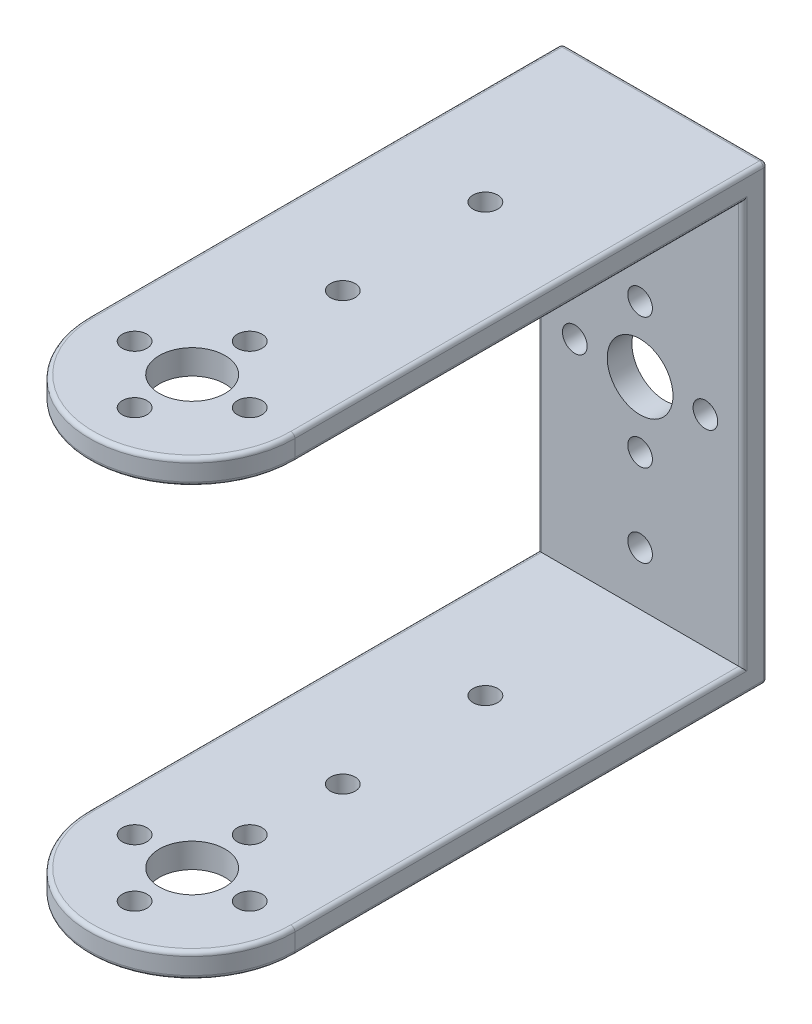
SolidWorks part; units mm, degrees
ref_plane "Front Plane" through (0, 0, 0) normal (0, 0, 1) x (1, 0, 0)
ref_plane "Top Plane" through (0, 0, 0) normal (0, 1, 0) x (1, 0, 0)
ref_plane "Right Plane" through (0, 0, 0) normal (1, 0, 0) x (0, 0, -1)
sketch "Sketch1" plane through (0, 0, 0) normal (0, 0, 1) x (1, 0, 0)
  line L1 (-12.5, 27.5) -> (12.5, 27.5)
  line L2 (-12.5, 27.5) -> (-12.5, -27.5)
  line L3 (-12.5, -27.5) -> (12.5, -27.5)
  line L4 (12.5, 27.5) -> (12.5, -27.5)
  line L5 (-12.5, 27.5) -> (12.5, -27.5) construction
  line L6 (-12.5, -27.5) -> (12.5, 27.5) construction
  point P0 (0, 0)
  dimension "D1" = 25
  dimension "D2" = 55
extrude "Boss-Extrude1" add sketch "Sketch1" along normal blind 3
hole_wizard "Ø8.0mm Dowel Hole1" positions "Sketch2" profile "Sketch3" hole size "Ø8.0" standard "ISO"
sketch "Sketch2" plane through (0, 0, 3) normal (0, 0, 1) x (1, 0, 0)
  point P0 (0, 0)
sketch "Sketch3" plane through (0, 0, 3) normal (1, 0, 0) x (0, -1, 0)
  line L0 (0, 0) -> (0, 5.4034)
  line L1 (0, 5.4034) -> (4, 3)
  line L2 (4, 3) -> (4, 0)
  line L5 (4, 0) -> (0, 0)
  line L10 (0, 5.4034) -> (-4, 3) construction
  line L11 (0, -6.35) -> (0, 107.95) construction
  dimension "Hole Dia." = 8
  dimension "Hole Depth" = 3
  dimension "Drill Angle" = 118
hole_wizard "Ø3.0mm Dowel Hole1" positions "Sketch4" profile "Sketch5" hole size "Ø3.0" standard "ISO"
sketch "Sketch4" plane through (0, 0, 3) normal (0, 0, 1) x (1, 0, 0)
  point P0 (0, -7.9463)
  point P6 (-7.9463, 0)
  point P7 (0, 7.9463)
  point P8 (7.9463, 0)
  point P9 (0, 0)
  point P10 (0, 18)
  point P18 (0, -36)
  point P19 (0, -18)
  dimension "D2" = 18
  dimension "D3" = 2
  dimension "D1" = 4
sketch "Sketch5" plane through (0, -7.9463, 3) normal (1, 0, 0) x (0, -1, 0)
  line L0 (0, 0) -> (0, 3.9013)
  line L1 (0, 3.9013) -> (1.5, 3)
  line L2 (1.5, 3) -> (1.5, 0)
  line L5 (1.5, 0) -> (0, 0)
  line L10 (0, 3.9013) -> (-1.5, 3) construction
  line L11 (0, -6.35) -> (0, 107.95) construction
  dimension "Hole Dia." = 3
  dimension "Hole Depth" = 3
  dimension "Drill Angle" = 118
sketch "Sketch6" plane through (0, 0, 3) normal (0, 0, 1) x (1, 0, 0)
  line L0 (12.5, -27.5) -> (12.5, 27.5) construction
  line L1 (-12.5, 27.5) -> (12.5, 27.5)
  line L2 (-12.5, 27.5) -> (-12.5, 24.5)
  line L3 (-12.5, 24.5) -> (12.5, 24.5)
  line L4 (12.5, 27.5) -> (12.5, 24.5)
  line L5 (-12.5, -24.5) -> (-12.5, -27.5)
  line L6 (-12.5, -24.5) -> (12.5, -24.5)
  line L7 (12.5, -24.5) -> (12.5, -27.5)
  line L8 (-12.5, -27.5) -> (12.5, -27.5)
  dimension "D1" = 3
  dimension "D2" = 2
extrude "Boss-Extrude2" add sketch "Sketch6" along normal blind 67
sketch "Sketch8" plane through (0, 27.5, 0) normal (0, 1, 0) x (1, 0, 0)
  line L2 (-12.5, -70) -> (12.5, -70)
  line L3 (-12.5, -70) -> (-12.5, -57.5)
  line L5 (12.5, -70) -> (12.5, -57.5)
  arc A0 (-12.5, -57.5) -> (12.5, -57.5) centre (0, -57.5) ccw
  line M4 (-12.5, 0) -> (-12.5, -70)
  line M5 (-12.5, -70) -> (12.5, -70)
  line M6 (12.5, -70) -> (12.5, 0)
extrude "Cut-Extrude2" cut sketch "Sketch8" against normal through all contours A0 M4 M5 | A0 L2 M6
hole_wizard "Ø8.0mm Dowel Hole2" positions "Sketch9" profile "Sketch11" hole size "Ø8.0" standard "ISO" end condition through all
sketch "Sketch9" plane through (0, 27.5, 0) normal (0, 1, 0) x (1, 0, 0)
  point P0 (0, -57.5)
sketch "Sketch11" plane through (0, 27.5, 57.5) normal (1, 0, 0) x (0, 0, 1)
  line L0 (0, 0) -> (0, 55)
  line L1 (0, 55) -> (4, 55)
  line L2 (4, 55) -> (4, 0)
  line L5 (4, 0) -> (0, 0)
  line L11 (0, -6.35) -> (0, 107.95) construction
  dimension "Thru Hole Dia." = 8
  dimension "Thru Hole Depth" = 55
hole_wizard "Ø3.0mm Dowel Hole2" positions "Sketch12" profile "Sketch13" hole size "Ø3.0" standard "ISO" end condition through all
sketch "Sketch12" plane through (0, 27.5, 0) normal (0, 1, 0) x (1, 0, 0)
  circle A0 centre (0, -57.5) radius 4 construction
  point P24 (0.3262, -39.5)
  point P26 (-0.3262, -21.5)
  point P30 (0, -57.5)
  point P33 (0, -50.5)
  point P41 (7, -57.5)
  point P42 (0, -64.5)
  point P43 (-7, -57.5)
  point P44 (0, -57.5)
  dimension "D3" = 18
  dimension "D1" = 7
  dimension "D4" = 18
sketch "Sketch13" plane through (0, 27.5, 57.5) normal (1, 0, 0) x (0, 0, 1)
  line L0 (0, 0) -> (0, 55)
  line L1 (0, 55) -> (1.5, 55)
  line L2 (1.5, 55) -> (1.5, 0)
  line L5 (1.5, 0) -> (0, 0)
  line L11 (0, -6.35) -> (0, 107.95) construction
  dimension "Thru Hole Dia." = 3
  dimension "Thru Hole Depth" = 55
fillet "Fillet2" radius 0.5 18 edges at (12.5, -24.5, 30.25) (12.5, 0, 3) (12.5, 24.5, 30.25) (12.5, 27.5, 28.75) (12.5, 0, 0) (12.5, -27.5, 28.75) (0, 27.5, 70) (0, 24.5, 70) (0, -27.5, 0) (0, 27.5, 0) (-12.5, 0, 3) (0, -24.5, 70) (0, -27.5, 70) (-12.5, 24.5, 30.25) (-12.5, 27.5, 28.75) (-12.5, -24.5, 30.25) (-12.5, -27.5, 28.75) (-12.5, 0, 0)
